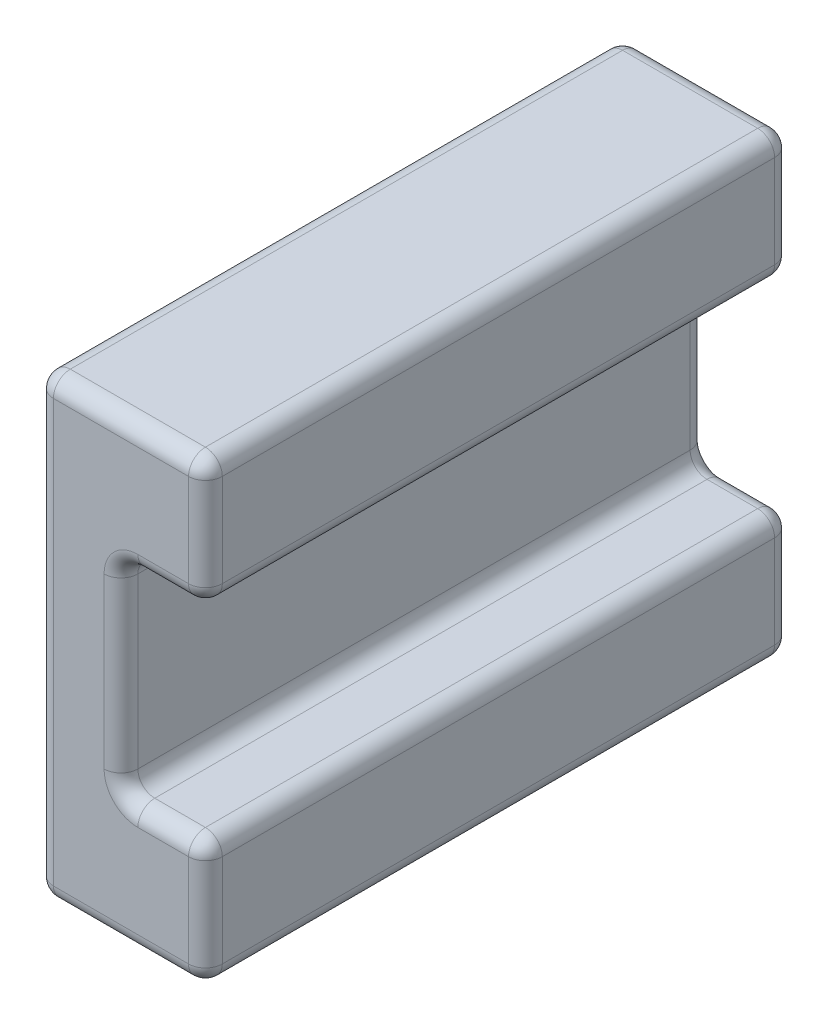
SolidWorks part; units mm, degrees
ref_plane "Front Plane" through (0, 0, 0) normal (0, 0, 1) x (1, 0, 0)
ref_plane "Top Plane" through (0, 0, 0) normal (0, 1, 0) x (1, 0, 0)
ref_plane "Right Plane" through (0, 0, 0) normal (1, 0, 0) x (0, 0, -1)
sketch "Sketch1" plane through (0, 0, 0) normal (0, 0, 1) x (1, 0, 0)
  line L0 (5, -6) -> (5, -13.5)
  line L1 (-5, 13.5) -> (5, 13.5)
  line L2 (-5, 13.5) -> (-5, -13.5)
  line L3 (-5, -13.5) -> (5, -13.5)
  line L4 (5, 13.5) -> (5, 6)
  line L5 (-5, 13.5) -> (5, -13.5) construction
  line L6 (-5, -13.5) -> (5, 13.5) construction
  line L7 (0, -6) -> (5, -6)
  line L8 (0, -6) -> (0, 6)
  line L9 (0, 6) -> (5, 6)
  line L11 (0, -6) -> (5, 0) construction
  line L12 (0, 6) -> (5, 0) construction
  point P0 (0, 0)
  point P6 (5, 0)
  dimension "D1" = 27
  dimension "D2" = 10
  dimension "D3" = 12
  dimension "D4" = 5
extrude "Boss-Extrude1" add sketch "Sketch1" along normal blind 34.7
sketch "Sketch3" plane through (-5, 0, 0) normal (-1, 0, 0) x (0, 0, 1)
  line L0 (0, 0) -> (5.5023, 0) construction
  line L1 (17.35, 15.8594) -> (17.35, 13.4331) construction
  circle A0 centre (9.85, 10) radius 1.7
  circle A1 centre (24.85, 10) radius 1.7
  circle A2 centre (24.85, -10) radius 1.7
  circle A3 centre (9.85, -10) radius 1.7
  dimension "D1" = 3.4
  dimension "D2" = 15
  dimension "D3" = 20
fillet "Fillet1" radius 1 24 edges at (-5, -13.5, 17.35) (2.5, -6, 0) (2.5, 6, 0) (-5, 0, 0) (0, -13.5, 0) (-5, 0, 34.7) (2.5, 6, 34.7) (2.5, -6, 34.7) (0, -13.5, 34.7) (0, -6, 17.35) (0, 0, 34.7) (0, 6, 17.35) (0, 0, 0) (5, -13.5, 17.35) (5, -9.75, 34.7) (5, -6, 17.35) (5, -9.75, 0) (5, 6, 17.35) (5, 9.75, 34.7) (5, 9.75, 0) (5, 13.5, 17.35) (0, 13.5, 34.7) (-5, 13.5, 17.35) (0, 13.5, 0)
hole_wizard "M3 Tapped Hole2" positions "3DSketch2" profile "Sketch5" tap size "M3" standard "ISO"
sketch3d "3DSketch2"
  point P0 (-5, 10, 9.85)
  point P3 (-5, 10, 24.85)
  point P6 (-5, -10, 24.85)
  point P9 (-5, -10, 9.85)
sketch "Sketch5" plane through (-5, 10, 9.85) normal (0, 1, 0) x (0, 0, 1)
  line L0 (0, 0) -> (0, 5)
  line L1 (0, 5) -> (1.25, 4.2489)
  line L2 (1.25, 4.2489) -> (1.25, 0.275)
  line L3 (1.25, 0.275) -> (1.525, 0)
  line L5 (1.525, 0) -> (0, 0)
  line L6 (-1.25, 0.275) -> (-1.525, 0) construction
  line L10 (0, 5) -> (-1.25, 4.2489) construction
  line L11 (0, -6.35) -> (0, 107.95) construction
  dimension "Tap Drill Dia." = 2.5
  dimension "Tap Drill Depth" = 5
  dimension "Near C'Sink Dia." = 3.05
  dimension "Near C'Sink Angle" = 90
  dimension "Drill Angle" = 118
cosmetic thread "Hole Thread5" parameters "D1"=6, "D2"=3
cosmetic thread "Hole Thread6" parameters "D1"=6, "D2"=3
cosmetic thread "Hole Thread7" parameters "D1"=6, "D2"=3
cosmetic thread "Hole Thread8" parameters "D1"=6, "D2"=3
sketch "Sketch6" plane through (-5, 0, 0) normal (-1, 0, 0) x (0, 0, 1)
  circle A0 centre (9.85, 10) radius 1.75
  circle A1 centre (24.85, 10) radius 1.9
  circle A2 centre (9.85, -10) radius 1.9
  circle A3 centre (24.85, -10) radius 1.9
  dimension "D1" = 3.5
  dimension "D2" = 3.8
  dimension "D3" = 3.8
  dimension "D4" = 3.8
